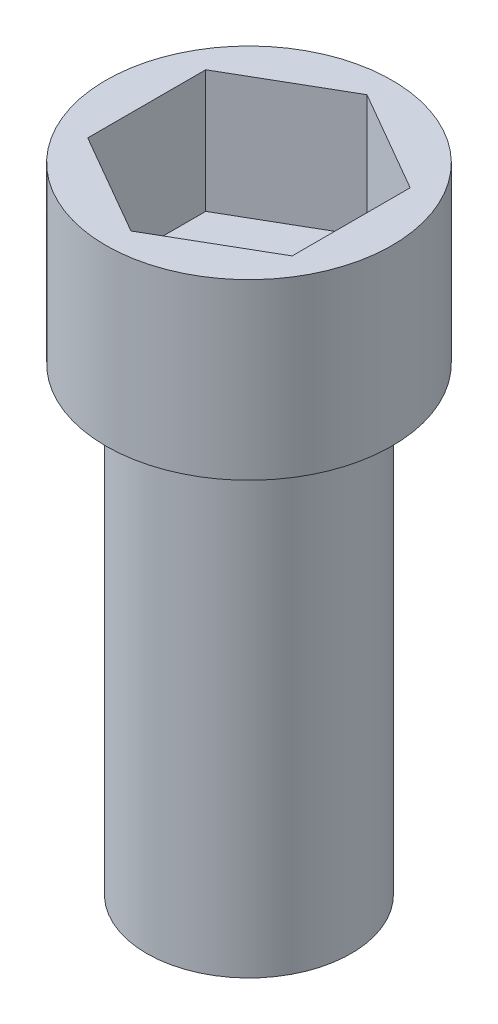
SolidWorks part; units mm, degrees
ref_plane "Front Plane" through (0, 0, 0) normal (0, 0, 1) x (1, 0, 0)
ref_plane "Top Plane" through (0, 0, 0) normal (0, 1, 0) x (1, 0, 0)
ref_plane "Right Plane" through (0, 0, 0) normal (1, 0, 0) x (0, 0, -1)
sketch "Sketch1" plane through (0, 0, 0) normal (0, 1, 0) x (1, 0, 0)
  circle A0 centre (0, 0) radius 14
  dimension "D1" = 28
extrude "Boss-Extrude1" add sketch "Sketch1" along normal blind 17
sketch "Sketch2" plane through (0, 0, 0) normal (0, -1, 0) x (1, 0, 0)
  circle A0 centre (0, 0) radius 10
  dimension "D1" = 20
extrude "Boss-Extrude2" add sketch "Sketch2" along normal blind 45
sketch "Sketch3" plane through (0, 17, 0) normal (0, 1, 0) x (1, 0, 0)
  line L1 (10, 5.7735) -> (0, 11.547)
  line L2 (0, 11.547) -> (-10, 5.7735)
  line L3 (-10, 5.7735) -> (-10, -5.7735)
  line L4 (-10, -5.7735) -> (0, -11.547)
  line L5 (0, -11.547) -> (10, -5.7735)
  line L6 (10, -5.7735) -> (10, 5.7735)
  circle A0 centre (0, 0) radius 10 construction
  point P1 (0, 0)
  dimension "D1" = 20
extrude "Cut-Extrude1" cut sketch "Sketch3" against normal blind 12
